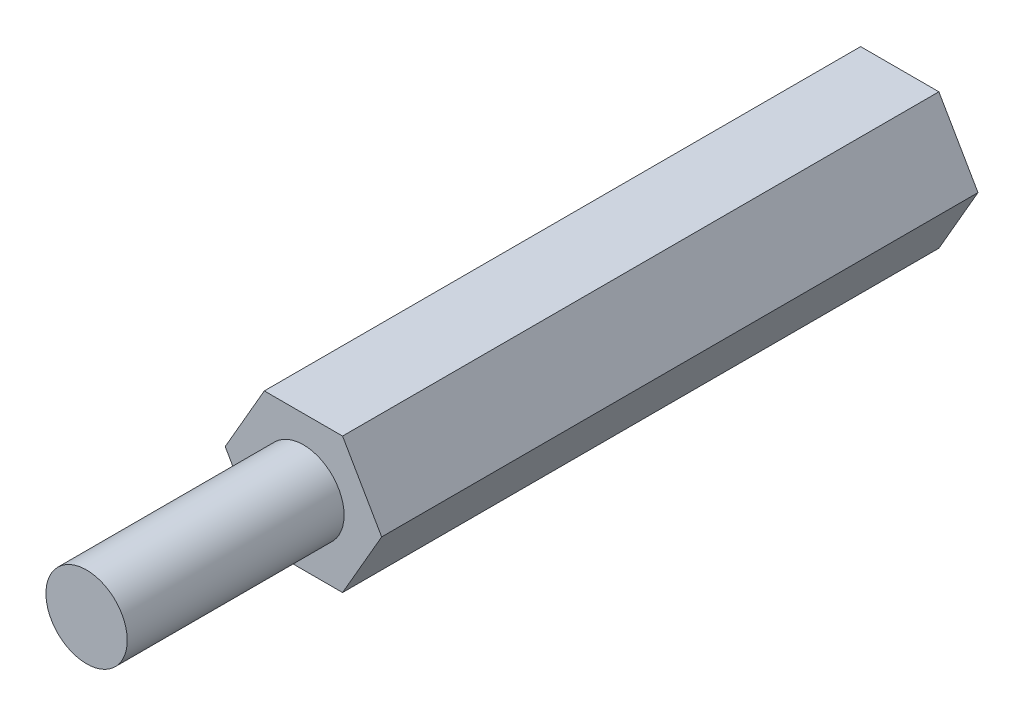
SolidWorks part; units mm, degrees
ref_plane "前视基准面" through (0, 0, 0) normal (0, 0, 1) x (1, 0, 0)
ref_plane "上视基准面" through (0, 0, 0) normal (0, 1, 0) x (1, 0, 0)
ref_plane "右视基准面" through (0, 0, 0) normal (1, 0, 0) x (0, 0, -1)
sketch "草图1" plane through (0, 0, 0) normal (0, 0, 1) x (1, 0, 0)
  line L0 (-28.6627, 0) -> (33.6774, 0) construction
  line L1 (1.4434, -2.5) -> (2.8868, 0)
  line L2 (2.8868, 0) -> (1.4434, 2.5)
  line L3 (1.4434, 2.5) -> (-1.4434, 2.5)
  line L4 (-1.4434, 2.5) -> (-2.8868, 0)
  line L5 (-2.8868, 0) -> (-1.4434, -2.5)
  line L6 (-1.4434, -2.5) -> (1.4434, -2.5)
  circle A0 centre (0, 0) radius 2.5 construction
  dimension "D1" = 5
extrude "拉伸1" add sketch "草图1" along normal blind 22
sketch "草图2" plane through (0, 0, 22) normal (0, 0, 1) x (1, 0, 0)
  circle A0 centre (0, 0) radius 1.5
  dimension "D1" = 3
extrude "拉伸2" add sketch "草图2" along normal blind 8
hole_wizard "M3x0.5 螺纹孔1" positions "3D草图2" profile "草图5" tap size "M3x0.5" standard "ISO"
sketch3d "3D草图2"
  point P0 (0, 0, 0)
  point P2 (0, 0, 0)
  point P3 (0, 0, 0)
  point P4 (0, 0, 0)
sketch "草图5" plane through (0, 0, 0) normal (1, 0, 0) x (0, 1, 0)
  line L0 (0, 0) -> (0, 11.7511)
  line L1 (0, 11.7511) -> (1.25, 11)
  line L2 (1.25, 11) -> (1.25, 0)
  line L5 (1.25, 0) -> (0, 0)
  line L10 (0, 11.7511) -> (-1.25, 11) construction
  line L11 (0, -6.35) -> (0, 107.95) construction
  dimension "蹟恇謂郰芛眻噤" = 2.5
  dimension "蹟恇謂郰芛旮僅" = 11
  dimension "絳芛褒僅" = 118
cosmetic thread "孔螺蚊线1" parameters "D1"=6, "D2"=3
